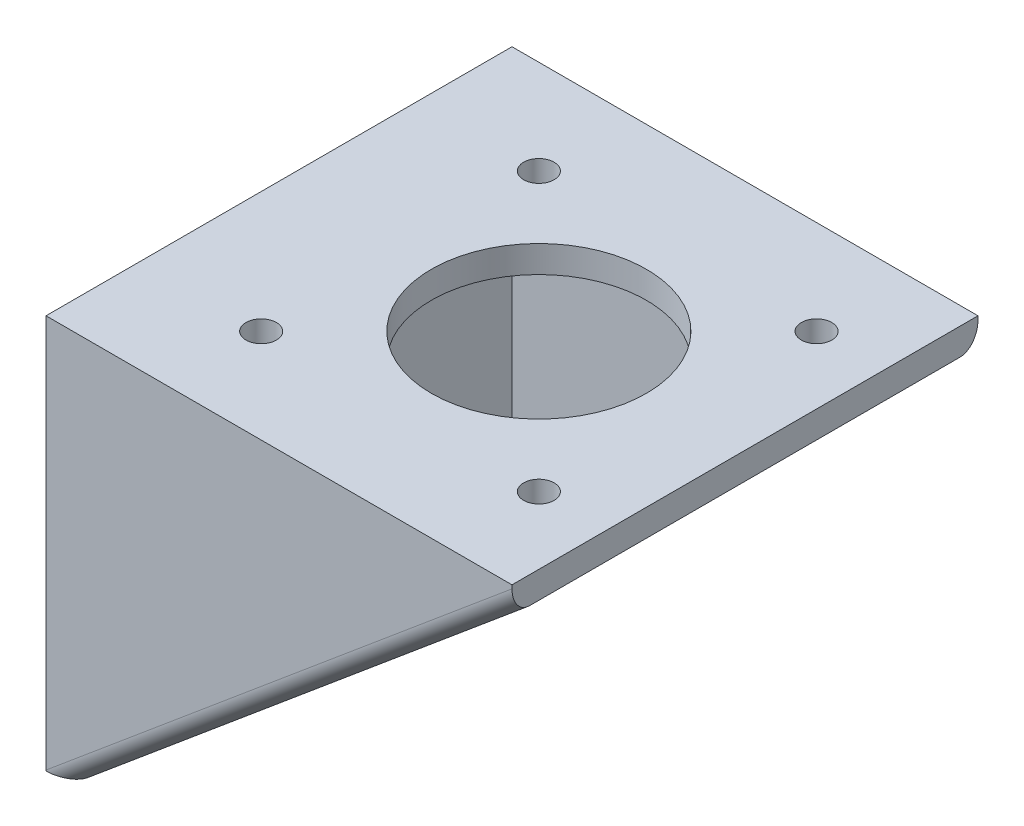
SolidWorks part; units mm, degrees
material "ABS"
ref_plane "Front Plane" through (0, 0, 0) normal (0, 0, 1) x (1, 0, 0)
ref_plane "Top Plane" through (0, 0, 0) normal (0, 1, 0) x (1, 0, 0)
ref_plane "Right Plane" through (0, 0, 0) normal (1, 0, 0) x (0, 0, -1)
sketch "Sketch1" plane through (0, 0, 0) normal (0, 1, 0) x (1, 0, 0)
  line L0 (-29, 26) -> (23, 26)
  line L1 (23, 26) -> (23, -26)
  line L2 (23, -26) -> (-29, -26)
  line L3 (-29, -26) -> (-29, 26)
  line L5 (0, 0) -> (-29, 0) construction
  circle A0 centre (0, 0) radius 12
  dimension "D1" = 24
  dimension "D2" = 52
  dimension "D3" = 52
  dimension "D4" = 29
extrude "Boss-Extrude1" add sketch "Sketch1" along normal blind 3
sketch "Sketch2" plane through (-29, 0, 0) normal (-1, 0, 0) x (0, 0, 1)
  line L0 (-26, 3) -> (26, 3) construction
  line L1 (-26, 0) -> (26, 0)
  line L2 (-26, 0) -> (-26, -41)
  line L3 (-26, -41) -> (26, -41)
  line L4 (26, 0) -> (26, -41)
  line L5 (26, 3) -> (26, 0) construction
  dimension "D1" = 44
extrude "Boss-Extrude2" add sketch "Sketch2" against normal blind 3
hole_wizard "M3 Clearance Hole1" positions "Sketch3" profile "Sketch4" hole size "M3" standard "ANSI Metric" end condition through all
sketch "Sketch3" plane through (0, 3, 0) normal (0, 1, 0) x (1, 0, 0)
  line L0 (15.494, -15.494) -> (-15.494, -15.494) construction
  line L1 (-15.494, -15.494) -> (-15.494, 15.494) construction
  line L2 (-15.494, 15.494) -> (15.494, 15.494) construction
  line L3 (15.494, 15.494) -> (15.494, -15.494) construction
  line L5 (0, 15.494) -> (0, -15.494) construction
  line L7 (15.494, 0) -> (-15.494, 0) construction
  point P0 (15.494, -15.494)
  point P2 (-15.494, -15.494)
  point P4 (-15.494, 15.494)
  point P6 (15.494, 15.494)
  dimension "D1" = 30.988
  dimension "D2" = 30.988
sketch "Sketch4" plane through (15.494, 3, 15.494) normal (1, 0, 0) x (0, 0, 1)
  line L0 (0, 0) -> (0, 44)
  line L1 (0, 44) -> (1.7, 44)
  line L2 (1.7, 44) -> (1.7, 0)
  line L5 (1.7, 0) -> (0, 0)
  line L11 (0, -6.35) -> (0, 107.95) construction
  dimension "Thru Hole Dia." = 3.4
  dimension "Thru Hole Depth" = 44
hole_wizard "M4 Clearance Hole1" positions "Sketch5" profile "Sketch6" hole size "M4" standard "ANSI Metric" end condition through all
sketch "Sketch5" plane through (-26, 0, 0) normal (1, 0, 0) x (0, 0, -1)
  line L0 (-10, -9) -> (-10, -31) construction
  line L1 (-10, -31) -> (10, -31) construction
  line L2 (10, -31) -> (10, -9) construction
  line L3 (10, -9) -> (-10, -9) construction
  line L7 (26, -41) -> (-26, -41) construction
  line L9 (-26, 3) -> (-26, -41) construction
  point P0 (-10, -9)
  point P2 (10, -9)
  point P4 (10, -31)
  point P6 (-10, -31)
  point P31 (0, -9)
  point P33 (0, -31)
  dimension "D1" = 20
  dimension "D2" = 22
  dimension "D3" = 10
  dimension "D4" = 16
sketch "Sketch6" plane through (-26, -9, 10) normal (0, 1, 0) x (0, 0, -1)
  line L0 (0, 0) -> (0, 3)
  line L1 (0, 3) -> (2.25, 3)
  line L2 (2.25, 3) -> (2.25, 0)
  line L5 (2.25, 0) -> (0, 0)
  line L11 (0, -6.35) -> (0, 107.95) construction
  dimension "Thru Hole Dia." = 4.5
  dimension "Thru Hole Depth" = 3
sketch "Sketch7" plane through (0, 0, -26) normal (0, 0, -1) x (-1, 0, 0)
  line L0 (26, -41) -> (-23, 0)
  line L1 (26, 0) -> (26, -41) construction
  line L2 (-23, 0) -> (26, 0) construction
  line L3 (26, 0) -> (26, -41)
  line L4 (-23, 0) -> (26, 0)
extrude "Boss-Extrude3" add sketch "Sketch7" against normal blind 3
sketch "Sketch8" plane through (0, 0, 26) normal (0, 0, 1) x (1, 0, 0)
  line L0 (23, 0) -> (-26, -41)
  line L1 (-26, -41) -> (-26, 0) construction
  line L2 (-26, 0) -> (23, 0) construction
  line L3 (-26, -41) -> (-26, 0)
  line L4 (-26, 0) -> (23, 0)
extrude "Boss-Extrude4" add sketch "Sketch8" against normal blind 3
fillet "Fillet1" radius 2 2 edges at (-1.5, -20.5, 26) (-1.5, -20.5, -26)
